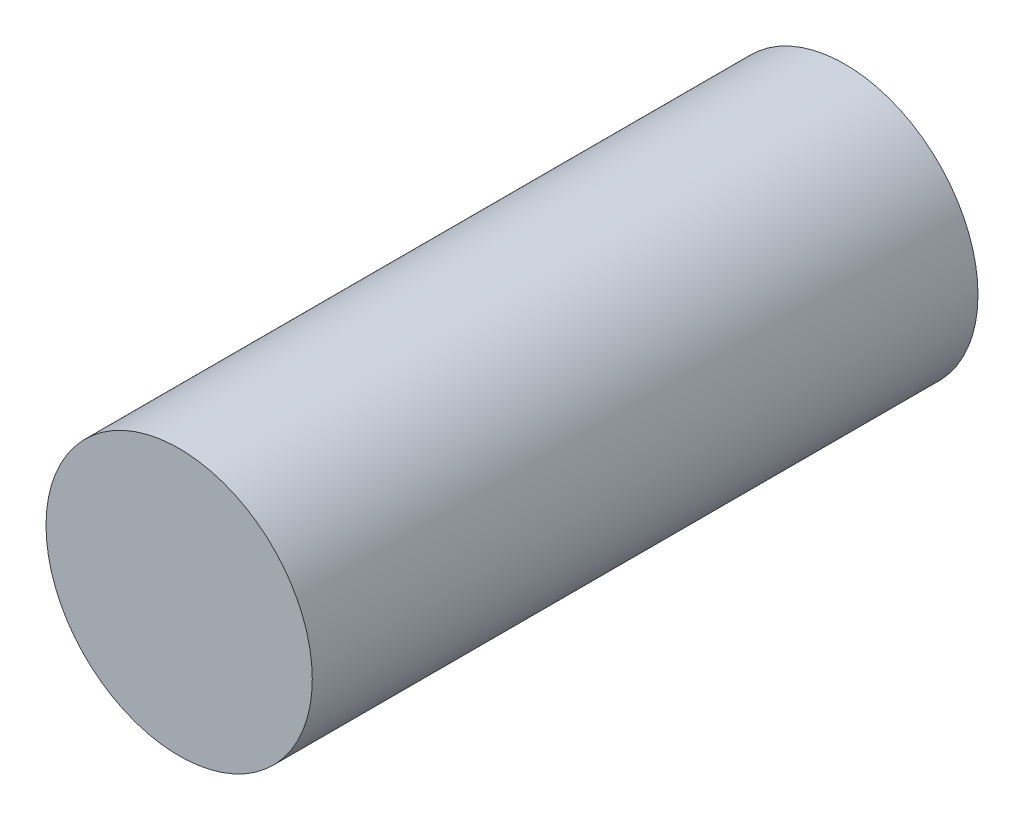
SolidWorks part; units mm, degrees
ref_plane "Front Plane" through (0, 0, 0) normal (0, 0, 1) x (1, 0, 0)
ref_plane "Top Plane" through (0, 0, 0) normal (0, 1, 0) x (1, 0, 0)
ref_plane "Right Plane" through (0, 0, 0) normal (1, 0, 0) x (0, 0, -1)
sketch "Sketch1" plane through (0, 0, 0) normal (0, 0, 1) x (1, 0, 0)
  circle A0 centre (0, 0) radius 4.7625
  dimension "D1" = 9.525
extrude "Boss-Extrude1" add sketch "Sketch1" along normal mid plane 23.8125
